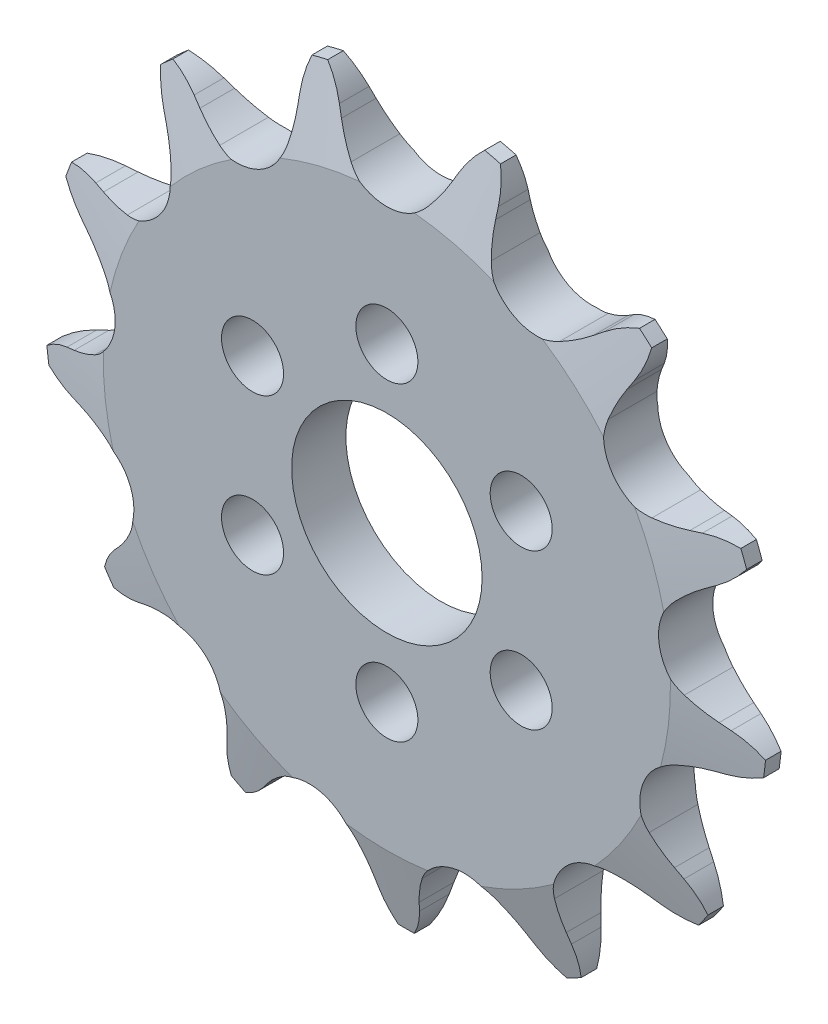
SolidWorks part; units mm, degrees
material "AISI 4130 Steel, annealed at 865C"
ref_plane "Front Plane" through (0, 0, 0) normal (0, 0, 1) x (1, 0, 0)
ref_plane "Top Plane" through (0, 0, 0) normal (0, 1, 0) x (1, 0, 0)
ref_plane "Right Plane" through (0, 0, 0) normal (1, 0, 0) x (0, 0, -1)
sketch "Sketch0" plane through (0, 0, 0) normal (0, 0, 1) x (1, 0, 0)
  line L0 (7.9375, -32.2037) -> (0, 0) construction
  line L1 (0, 0) -> (21.9941, -24.8262) construction
  line L2 (0, 0) -> (-7.9375, -32.2037) construction
  line L3 (7.9375, -32.2037) -> (21.9941, -24.8262) construction
  line L4 (7.9375, -32.2037) -> (-7.9375, -32.2037) construction
  line L5 (13.9545, -31.0679) -> (13.2815, -30.2592)
  line L6 (7.9375, -32.2037) -> (0, -34.1601) construction
  line L7 (2.0819, -33.9942) -> (2.302, -32.9654)
  line L8 (0, -32.2037) -> (0, -36.9662) construction
  line L9 (10.986, -28.0897) -> (3.0984, -38.7342) construction
  line L10 (0, 0) -> (0, -32.2037) construction
  line L11 (13.2815, -30.2592) -> (3.0984, -38.7342) construction
  line L12 (0, -36.9662) -> (0, -38.0102) construction
  line L13 (20.5322, -25.5935) -> (13.9545, -31.0679) construction
  circle A0 centre (0, 0) radius 36.9662 construction
  circle A1 centre (0, 0) radius 33.1675 construction
  arc A2 (-7.9261, -40.603) -> (25.8874, -32.2687) centre (0, 0) ccw
  circle A3 centre (0, 0) radius 38.0102 construction
  circle A4 centre (7.9375, -32.2037) radius 5.08 construction
  arc A7 (10.986, -28.0897) -> (3.3263, -29.9776) centre (7.9375, -32.2037) ccw
  circle A8 centre (7.9375, -32.2037) radius 5.1204 construction
  arc A9 (13.9545, -31.0679) -> (25.8874, -32.2687) centre (20.5322, -25.5935) ccw
  arc A10 (13.2815, -30.2592) -> (10.986, -28.0897) centre (3.0984, -38.7342) ccw
  arc A11 (2.0819, -33.9942) -> (-7.9261, -40.603) centre (-6.2865, -32.2037) cw
  arc A12 (2.302, -32.9654) -> (3.3263, -29.9776) centre (15.2572, -35.7373) cw
  dimension "D1" = 5.1204
  dimension "R" = 5.1204
sketch "Sketch1" plane through (0, 0, 0) normal (1, 0, 0) x (0, 0, -1)
  line L0 (2.7781, 0) -> (-2.7781, 0)
  line L1 (-2.7781, 0) -> (-2.7781, 29.0287)
  line L2 (-2.7781, 29.0287) -> (-0.7937, 36.9662)
  line L3 (-0.7937, 36.9662) -> (0.7937, 36.9662)
  line L4 (0.7937, 36.9662) -> (2.7781, 29.0287)
  line L5 (2.7781, 29.0287) -> (2.7781, 0)
  line L7 (0, 36.9662) -> (0, 0) construction
  line L8 (-2.7781, 29.0287) -> (2.7781, 29.0287) construction
  line L9 (0, 36.9662) -> (0, -36.9662) construction
  line L10 (-2.7781, 29.0287) -> (-2.7781, 36.9662) construction
  line L11 (-2.7781, 36.9662) -> (-0.7937, 36.9662) construction
  line L12 (0.7937, 36.9662) -> (2.7781, 36.9662) construction
  line L13 (2.7781, 36.9662) -> (2.7781, 29.0287) construction
revolve "Revolve1" add sketch "Sketch1" angle 360 mid plane about L0
extrude "Cut-Extrude1" cut sketch "Sketch0" against normal through all and the other way through all
pattern_circular "CirPattern1" count 13 over 360 about axis through (0, 0, 0) along (0, 0, 1) of "Cut-Extrude1"
sketch "Sketch2" plane through (0, 0, 0) normal (0, 0, 1) x (1, 0, 0)
  circle A0 centre (0, 0) radius 7.9375 construction
  circle A1 centre (0, 0) radius 30.1625
  circle A2 centre (0, 0) radius 36.957 construction
  dimension "Bore" = 15.875
  dimension "Hub Dia." = 60.325
  dimension "OD" = 73.914
sketch "Sketch3" plane through (0, 0, 0) normal (0, 0, 1) x (1, 0, 0)
  circle A1 centre (0, 0) radius 9.75
  circle A2 centre (0, 0) radius 36.957 construction
  circle A3 centre (0, 0) radius 36.957
extrude "Cut-Extrude2" cut sketch "Sketch3" along normal through all and the other way through all flip side to cut
sketch "Sketch4" plane through (0, 0, -2.7781) normal (0, 0, -1) x (-1, 0, 0)
  line L0 (0, 0) -> (0, 15.875) construction
  circle A0 centre (0, 15.875) radius 3.175
  circle A1 centre (13.7482, 7.9375) radius 3.175
  circle A2 centre (13.7482, -7.9375) radius 3.175
  circle A3 centre (0, -15.875) radius 3.175
  circle A4 centre (-13.7482, -7.9375) radius 3.175
  circle A5 centre (-13.7482, 7.9375) radius 3.175
  point P17 (0, 0)
  dimension "D1" = 6
extrude "Cut-Extrude3" cut sketch "Sketch4" against normal through all
sketch "Sketch5" plane through (0, 0, 2.7781) normal (0, 0, 1) x (1, 0, 0)
  line L0 (0, 0) -> (9.75, 0) construction
  line L1 (9.75, 0) -> (11, 0) construction
  circle A0 centre (0, 0) radius 11 construction
  circle A1 centre (0, 0) radius 9.75 construction
sketch "Sketch6" plane through (0, 0, -2.7781) normal (0, 0, -1) x (-1, 0, 0)
  circle A0 centre (0, 0) radius 28.024 construction
  circle A1 centre (0, 0) radius 24.2521 construction
ref_plane "Plane1" through (-29.6883, 20.4924, 0) normal (-0.823, 0.5681, 0) x (0, 0, 1)
ref_plane "Plane2" through (-35.811, 4.3482, 0) normal (-0.9927, 0.1205, 0) x (0, 0, 1)
ref_plane "Plane3" through (-33.7298, -12.792, 0) normal (-0.935, -0.3546, 0) x (0, 0, 1)
ref_plane "Plane4" through (-23.9215, -27.0018, 0) normal (-0.6631, -0.7485, 0) x (-0.7485, 0.6631, 0)
ref_plane "Plane5" through (-8.6331, -35.0258, 0) normal (-0.2393, -0.9709, 0) x (-0.9709, 0.2393, 0)
sketch "Sketch7" plane through (-29.6883, 20.4924, 0) normal (-0.823, 0.5681, 0) x (0, 0, 1)
  line L0 (-6.5106, 0) -> (7.7601, 0)
sketch "Sketch8" plane through (-35.811, 4.3482, 0) normal (-0.9927, 0.1205, 0) x (0, 0, 1)
  line L0 (-7.786, 0) -> (10.2102, 0)
sketch "Sketch9" plane through (-33.7298, -12.792, 0) normal (-0.935, -0.3546, 0) x (0, 0, 1)
  line L0 (-7.6671, 0) -> (14.0341, 0)
  line L1 (-2.7781, 0) -> (2.7781, 0) construction
sketch "Sketch10" plane through (-23.9215, -27.0018, 0) normal (-0.6631, -0.7485, 0) x (-0.7485, 0.6631, 0)
  line L0 (0, -3.5829) -> (0, 5.4944)
sketch "Sketch11" plane through (-8.6331, -35.0258, 0) normal (-0.2393, -0.9709, 0) x (-0.9709, 0.2393, 0)
  line L0 (0, -5.4358) -> (0, 8.5188)
split line "Split Line7"
split line "Split Line8"
split line "Split Line9"
split line "Split Line10"
split line "Split Line11"
ref_plane "Motor Sprocket Middle Plane" through (0, 0, 1.6781) normal (0, 0, 1) x (1, 0, 0)
equation "\"360/N@Sketch0\" = 360/\"Teeth@CirPattern1\""
equation "\"Ds@Sketch0\" = 1.005 * \"Dr@Sketch0\" + 0.003"
equation "\"R@Sketch0\" = 1/2 * \"Ds@Sketch0\""
equation "\"A@Sketch0\" = 35 +  ( 60 / \"Teeth@CirPattern1\" ) "
equation "\"B@Sketch0\" = 18 -  ( 56 / \"Teeth@CirPattern1\" )"
equation "\"ac@Sketch0\" = 0.8 * \"Dr@Sketch0\""
equation "\"ab@Sketch0\" = 1.4 * \"Dr@Sketch0\""
equation "\"J@Sketch0\" = 0.3 * \"Pitch@Sketch0\""
equation "\"h@Sketch1\" = \"Pitch@Sketch0\" / 2"
equation "\"g@Sketch1\" = \"h@Sketch1\" / 4"
